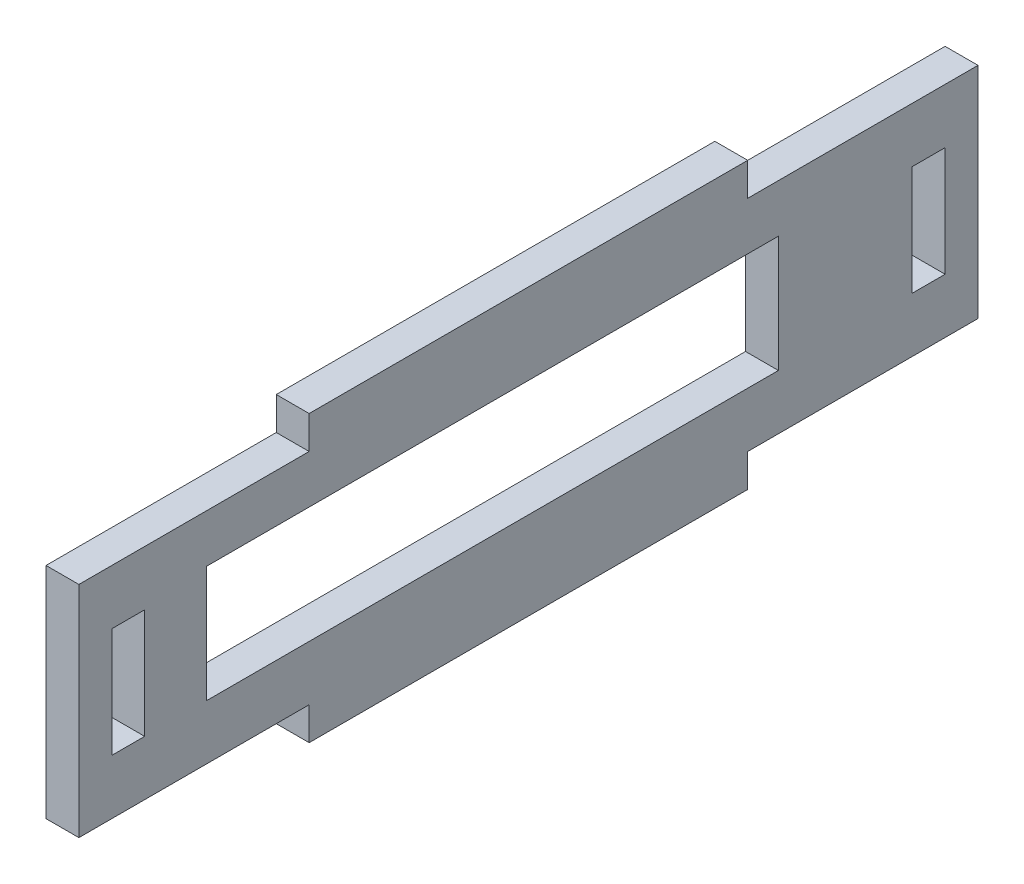
SolidWorks part; units mm, degrees
ref_plane "Front Plane" through (0, 0, 0) normal (0, 0, 1) x (1, 0, 0)
ref_plane "Top Plane" through (0, 0, 0) normal (0, 1, 0) x (1, 0, 0)
ref_plane "Right Plane" through (0, 0, 0) normal (1, 0, 0) x (0, 0, -1)
sketch "Sketch1" plane through (0, 0, 0) normal (1, 0, 0) x (0, 0, -1)
  line L0 (0, 0) -> (-6, 0) construction
  line L1 (0, 0) -> (70, 0) construction
  line L2 (0, 0) -> (0, 20) construction
  line L3 (0, 20) -> (70, 20) construction
  line L4 (70, 0) -> (70, 20) construction
  line L5 (70, 20) -> (76, 20) construction
  line L6 (0, 10) -> (-1.5, 10) construction
  line L11 (70, 10) -> (71.5, 10) construction
  line L12 (-3, 15) -> (0, 15)
  line L13 (-3, 15) -> (-3, 5)
  line L14 (-3, 5) -> (0, 5)
  line L15 (0, 15) -> (0, 5)
  line L16 (-3, 15) -> (0, 5) construction
  line L17 (-3, 5) -> (0, 15) construction
  line L18 (35, 20) -> (35, 21.5) construction
  line L19 (73, 15) -> (70, 15)
  line L20 (73, 15) -> (73, 5)
  line L21 (73, 5) -> (70, 5)
  line L22 (70, 15) -> (70, 5)
  line L23 (73, 15) -> (70, 5) construction
  line L24 (73, 5) -> (70, 15) construction
  line L25 (35, 0) -> (35, -1.5) construction
  line L26 (-6, 0) -> (-6, 20)
  line L27 (15, 23) -> (55, 23) construction
  line L28 (15, 23) -> (15, 20) construction
  line L29 (15, 20) -> (55, 20) construction
  line L30 (55, 23) -> (55, 20) construction
  line L31 (15, 23) -> (55, 20) construction
  line L32 (15, 20) -> (55, 23) construction
  line L33 (15, -3) -> (55, -3) construction
  line L34 (15, -3) -> (15, 0) construction
  line L35 (15, 0) -> (55, 0) construction
  line L36 (55, -3) -> (55, 0) construction
  line L37 (15, -3) -> (55, 0) construction
  line L38 (15, 0) -> (55, -3) construction
  line L39 (-6, 20) -> (15, 20)
  line L40 (15, 20) -> (15, 23)
  line L41 (15, 23) -> (55, 23)
  line L42 (55, 23) -> (55, 20)
  line L43 (55, 20) -> (76, 20)
  line L44 (76, 20) -> (76, 0)
  line L45 (76, 0) -> (55, 0)
  line L46 (55, -3) -> (15, -3)
  line L47 (15, 0) -> (-6, 0)
  line L48 (55, 0) -> (55, -3)
  line L49 (15, 0) -> (15, -3)
  line L51 (5.6214, 15.6109) -> (57.7987, 15.6109)
  line L52 (5.6214, 15.6109) -> (5.6214, 5)
  line L53 (5.6214, 5) -> (57.7987, 5)
  line L54 (57.7987, 15.6109) -> (57.7987, 5)
extrude "Boss-Extrude1" add sketch "Sketch1" along normal blind 3
